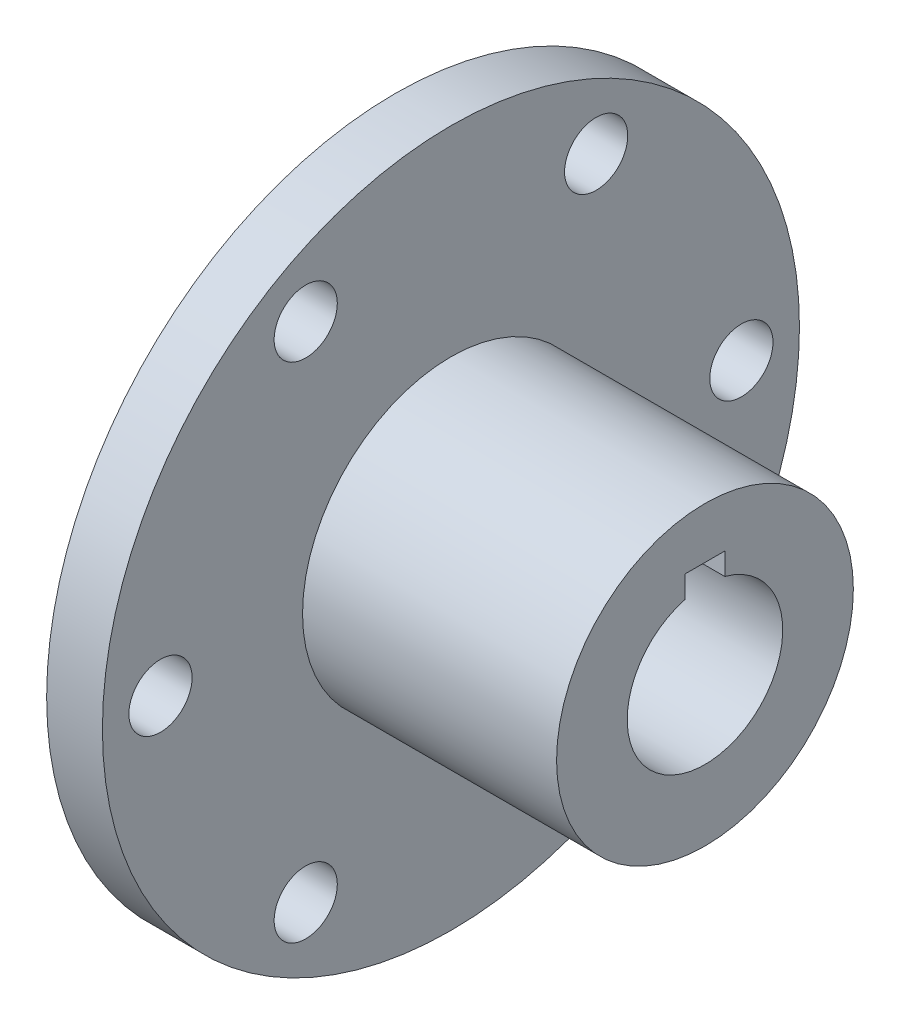
SolidWorks part; units mm, degrees
material "6061-T6 (SS)"
ref_plane "Front Plane" through (0, 0, 0) normal (0, 0, 1) x (1, 0, 0)
ref_plane "Top Plane" through (0, 0, 0) normal (0, 1, 0) x (1, 0, 0)
ref_plane "Right Plane" through (0, 0, 0) normal (1, 0, 0) x (0, 0, -1)
sketch "Sketch1" plane through (0, 0, 0) normal (0, 0, 1) x (1, 0, 0)
  line L0 (-17.6071, 28.575) -> (-17.6071, 0)
  line L1 (-17.6071, 0) -> (-13.0351, 0)
  line L2 (-13.0351, 0) -> (-13.0351, 28.575)
  line L3 (-13.0351, 28.575) -> (-17.6071, 28.575)
  line L4 (-17.6071, 0) -> (-13.0351, 0) construction
revolve "Revolve1" add sketch "Sketch1" angle 360 about L4
sketch "Sketch2" plane through (-13.0351, 0, 0) normal (1, 0, 0) x (0, 0, -1)
  circle A0 centre (0, 0) radius 12.1666
extrude "Extrude1" add sketch "Sketch2" along normal blind 20.828
sketch "Sketch3" plane through (-17.6071, 0, 0) normal (-1, 0, 0) x (0, 0, 1)
  line L0 (1.6256, 6.1647) -> (1.6256, 7.9756)
  line L1 (1.6256, 7.9756) -> (-1.6256, 7.9756)
  line L2 (-1.6256, 7.9756) -> (-1.6256, 6.1647)
  arc A0 (-1.6256, 6.1647) -> (1.6256, 6.1647) centre (0, 0) cw
extrude "Extrude2" cut sketch "Sketch3" against normal through all
ref_plane "Plane1" through (0, 0, 0) normal (0, 0, -1) x (-1, 0, 0)
sketch "Sketch4" plane through (0, 0, 0) normal (0, 0, -1) x (-1, 0, 0)
  line L0 (-7.7929, 6.3754) -> (-7.7929, 0)
  line L1 (-7.7929, 0) -> (17.6071, 0)
  line L2 (17.6071, 0) -> (17.6071, 6.3754)
  line L3 (17.6071, 6.3754) -> (-7.7929, 6.3754)
  line L4 (-7.7929, 0) -> (17.6071, 0) construction
revolve "Cut-Revolve1" cut sketch "Sketch4" angle 360 about L4
hole_wizard "Hole1" positions "Sketch6" profile "Sketch5" legacy
sketch "Sketch6" plane through (-17.6071, 0, 0) normal (-1, 0, 0) x (0, 0, 1)
  point P0 (11.9062, -20.6222)
sketch "Sketch5" plane through (-17.6071, -20.6222, 11.9062) normal (0, 1, 0) x (0, 0, 1)
  line L0 (0, 0) -> (0, 25.4)
  line L1 (0, 25.4) -> (2.5908, 25.4)
  line L2 (2.5908, 25.4) -> (2.5908, 0)
  line L3 (2.5908, 0) -> (0, 0)
  line L4 (0, 110) -> (0, -10) construction
  dimension "Diameter" = 5.1816
  dimension "Depth" = 25.4
hole_wizard "Hole2" positions "Sketch8" profile "Sketch7" legacy
sketch "Sketch8" plane through (-17.6071, 0, 0) normal (-1, 0, 0) x (0, 0, 1)
  point P0 (-11.9062, -20.6222)
sketch "Sketch7" plane through (-17.6071, -20.6222, -11.9062) normal (0, 1, 0) x (0, 0, 1)
  line L0 (0, 0) -> (0, 25.4)
  line L1 (0, 25.4) -> (2.5908, 25.4)
  line L2 (2.5908, 25.4) -> (2.5908, 0)
  line L3 (2.5908, 0) -> (0, 0)
  line L4 (0, 110) -> (0, -10) construction
  dimension "Diameter" = 5.1816
  dimension "Depth" = 25.4
hole_wizard "Hole3" positions "Sketch10" profile "Sketch9" legacy
sketch "Sketch10" plane through (-17.6071, 0, 0) normal (-1, 0, 0) x (0, 0, 1)
  point P0 (-23.8125, 0)
sketch "Sketch9" plane through (-17.6071, 0, -23.8125) normal (0, 1, 0) x (0, 0, 1)
  line L0 (0, 0) -> (0, 25.4)
  line L1 (0, 25.4) -> (2.5908, 25.4)
  line L2 (2.5908, 25.4) -> (2.5908, 0)
  line L3 (2.5908, 0) -> (0, 0)
  line L4 (0, 110) -> (0, -10) construction
  dimension "Diameter" = 5.1816
  dimension "Depth" = 25.4
hole_wizard "Hole4" positions "Sketch12" profile "Sketch11" legacy
sketch "Sketch12" plane through (-17.6071, 0, 0) normal (-1, 0, 0) x (0, 0, 1)
  point P0 (-11.9062, 20.6222)
sketch "Sketch11" plane through (-17.6071, 20.6222, -11.9062) normal (0, 1, 0) x (0, 0, 1)
  line L0 (0, 0) -> (0, 25.4)
  line L1 (0, 25.4) -> (2.5908, 25.4)
  line L2 (2.5908, 25.4) -> (2.5908, 0)
  line L3 (2.5908, 0) -> (0, 0)
  line L4 (0, 110) -> (0, -10) construction
  dimension "Diameter" = 5.1816
  dimension "Depth" = 25.4
hole_wizard "Hole5" positions "Sketch14" profile "Sketch13" legacy
sketch "Sketch14" plane through (-17.6071, 0, 0) normal (-1, 0, 0) x (0, 0, 1)
  point P0 (11.9062, 20.6222)
sketch "Sketch13" plane through (-17.6071, 20.6222, 11.9062) normal (0, 1, 0) x (0, 0, 1)
  line L0 (0, 0) -> (0, 25.4)
  line L1 (0, 25.4) -> (2.5908, 25.4)
  line L2 (2.5908, 25.4) -> (2.5908, 0)
  line L3 (2.5908, 0) -> (0, 0)
  line L4 (0, 110) -> (0, -10) construction
  dimension "Diameter" = 5.1816
  dimension "Depth" = 25.4
hole_wizard "Hole6" positions "Sketch16" profile "Sketch15" legacy
sketch "Sketch16" plane through (-17.6071, 0, 0) normal (-1, 0, 0) x (0, 0, 1)
  point P0 (23.8125, 0)
sketch "Sketch15" plane through (-17.6071, 0, 23.8125) normal (0, 1, 0) x (0, 0, 1)
  line L0 (0, 0) -> (0, 25.4)
  line L1 (0, 25.4) -> (2.5908, 25.4)
  line L2 (2.5908, 25.4) -> (2.5908, 0)
  line L3 (2.5908, 0) -> (0, 0)
  line L4 (0, 110) -> (0, -10) construction
  dimension "Diameter" = 5.1816
  dimension "Depth" = 25.4
